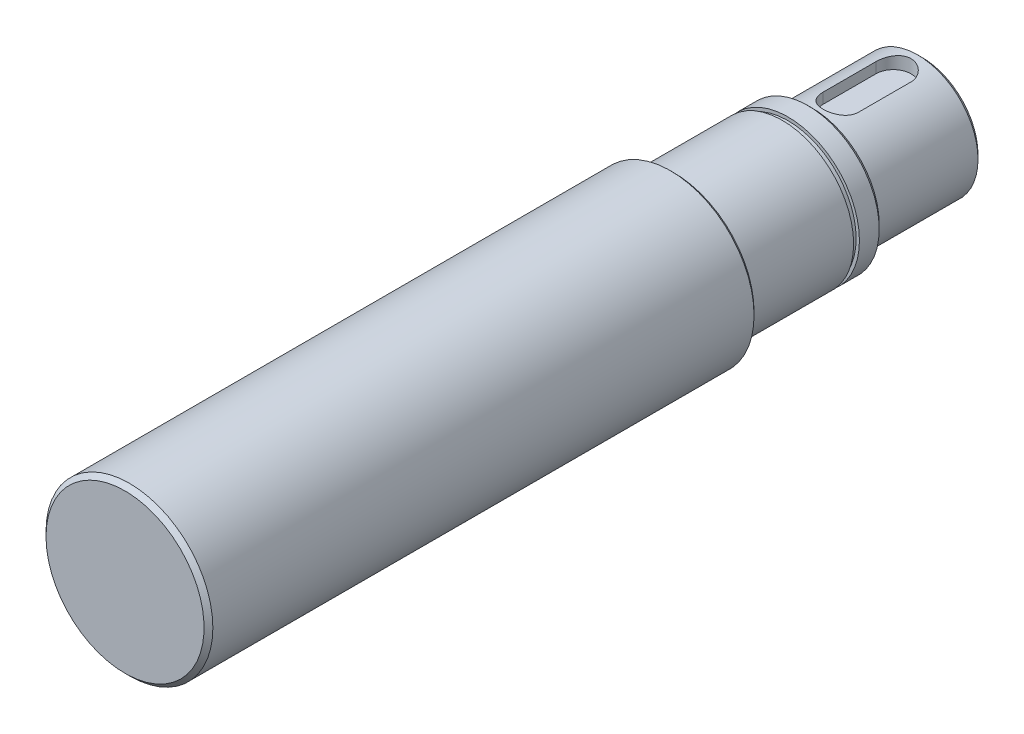
SolidWorks part; units mm, degrees
material "09Г2С ГОСТ 4543-71"
ref_plane "Спереди" through (0, 0, 0) normal (0, 0, 1) x (1, 0, 0)
ref_plane "Сверху" through (0, 0, 0) normal (0, 1, 0) x (1, 0, 0)
ref_plane "Справа" through (0, 0, 0) normal (1, 0, 0) x (0, 0, -1)
sketch "Эскиз1" plane through (0, 0, 0) normal (1, 0, 0) x (0, 0, -1)
  line L2 (0, 0) -> (0, 38)
  line L3 (0, 38) -> (250, 38)
  line L4 (250, 38) -> (250, 32.5)
  line L5 (250, 32.5) -> (299.35, 32.5)
  line L6 (313, 32.5) -> (313, 27.5)
  line L7 (313, 27.5) -> (363, 27.5)
  line L8 (363, 27.5) -> (363, 0)
  line L9 (0, 0) -> (363, 0)
  line L10 (-14.8991, 0) -> (296.3823, 0) construction
  line L11 (299.35, 32.5) -> (299.35, 31)
  line L12 (299.35, 31) -> (302, 31)
  line L13 (302, 31) -> (302, 32.5)
  line L14 (302, 32.5) -> (313, 32.5)
  dimension "D1" = 55
  dimension "D2" = 65
  dimension "D3" = 76
  dimension "D4" = 49.35
  dimension "D5" = 62
  dimension "D6" = 50
  dimension "D7" = 11
  dimension "D8" = 250
  dimension "D10" = 2.65
revolve "Повернуть1" add sketch "Эскиз1" angle 360 about L9
chamfer "Фаска1" distance 2 angle 45 2 edges at (38, 0, 0) (27.5, 0, -363)
sketch "Эскиз2" plane through (0, 0, -363) normal (0, 0, -1) x (-1, 0, 0)
  circle A0 centre (0, 0) radius 8
  dimension "D1" = 16
ref_plane "Плоскость1" through (0, 27.5, 0) normal (0, 1, 0) x (1, 0, 0)
chamfer "Фаска2" distance 1.5 angle 45 1 edges at (38, 0, -250)
sketch "Эскиз8" plane through (-6.6, 27.5, -280) normal (0, -1, 0) x (-1, 0, 0)
  line L0 (-6.6, 83) -> (-6.6, 70) construction
  line L1 (1.4, 83) -> (-14.6, 83) construction
  line L4 (-6.6, 70) -> (-6.6, 46) construction
  line L5 (1.4, 70) -> (1.4, 46)
  line L6 (-14.6, 70) -> (-14.6, 46)
  arc A0 (1.4, 70) -> (-14.6, 70) centre (-6.6, 70) ccw
  arc A1 (-14.6, 46) -> (1.4, 46) centre (-6.6, 46) ccw
  point P9 (-6.6, 58)
  point P15 (-6.6, 78)
  point P16 (-6.6, 38)
  dimension "D1" = 13
  dimension "D3" = 24
  dimension "D4" = 16
  dimension "D5" = 40
extrude "Вырез-Вытянуть1" cut sketch "Эскиз8" along normal blind 6 contours L5 A1 L6 A0
chamfer "Фаска3" distance 2 angle 45 1 edges at (32.5, 0, -313)
